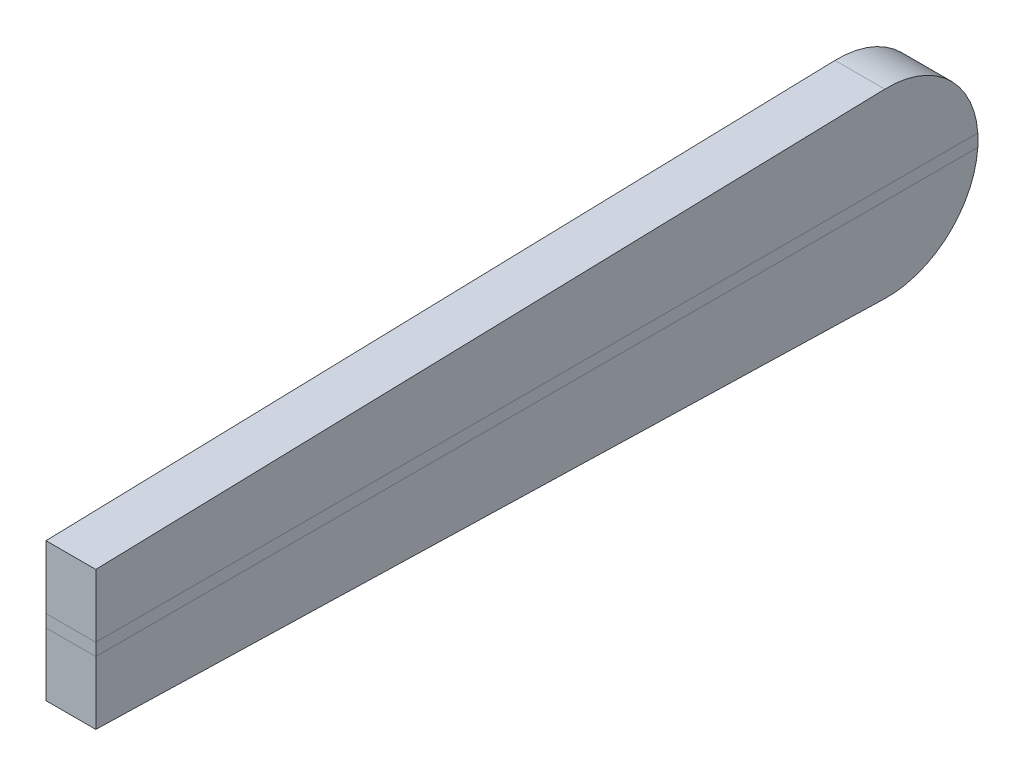
SolidWorks part; units mm, degrees
ref_plane "Alzado" through (0, 0, 0) normal (1, 0, 0) x (0, 1, 0)
ref_plane "Planta" through (0, 0, 0) normal (0, 0, 1) x (0, 1, 0)
ref_plane "Vista lateral" through (0, 0, 0) normal (0, 1, 0) x (-1, 0, 0)
sketch "Croquis5" plane through (0, 0, 0) normal (1, 0, 0) x (0, 1, 0)
  line L0 (-15.615, 99.415) -> (15.615, 99.415)
  line L1 (15.615, 99.415) -> (20.4475, -78.4043)
  line L2 (-20.4475, -78.4043) -> (-15.615, 99.415)
  arc A0 (-20.4475, -78.4043) -> (20.4475, -78.4043) centre (0, -78.96) ccw
extrude "Saliente-Extruir2" add sketch "Croquis5" along normal blind 11.22
sketch "Croquis9" plane through (11.22, 0, 0) normal (1, 0, 0) x (0, 1, 0)
  line L0 (0, 99.415) -> (0, -99.415)
sketch "Croquis10" plane through (0, 0, 0) normal (1, 0, 0) x (0, 1, 0)
  line L0 (-1.4, 101.415) -> (-1.4, -101.415)
  line L1 (1.4, 101.415) -> (1.4, -101.415)
split line "Línea de partición71"
sketch "Croquis11" plane through (0, 0, 0) normal (0, 0, 1) x (0, 1, 0)
  line L0 (-1.4, 2) -> (-1.4, -13.22)
  line L1 (1.4, 2) -> (1.4, -13.22)
split line "Línea de partición72"
